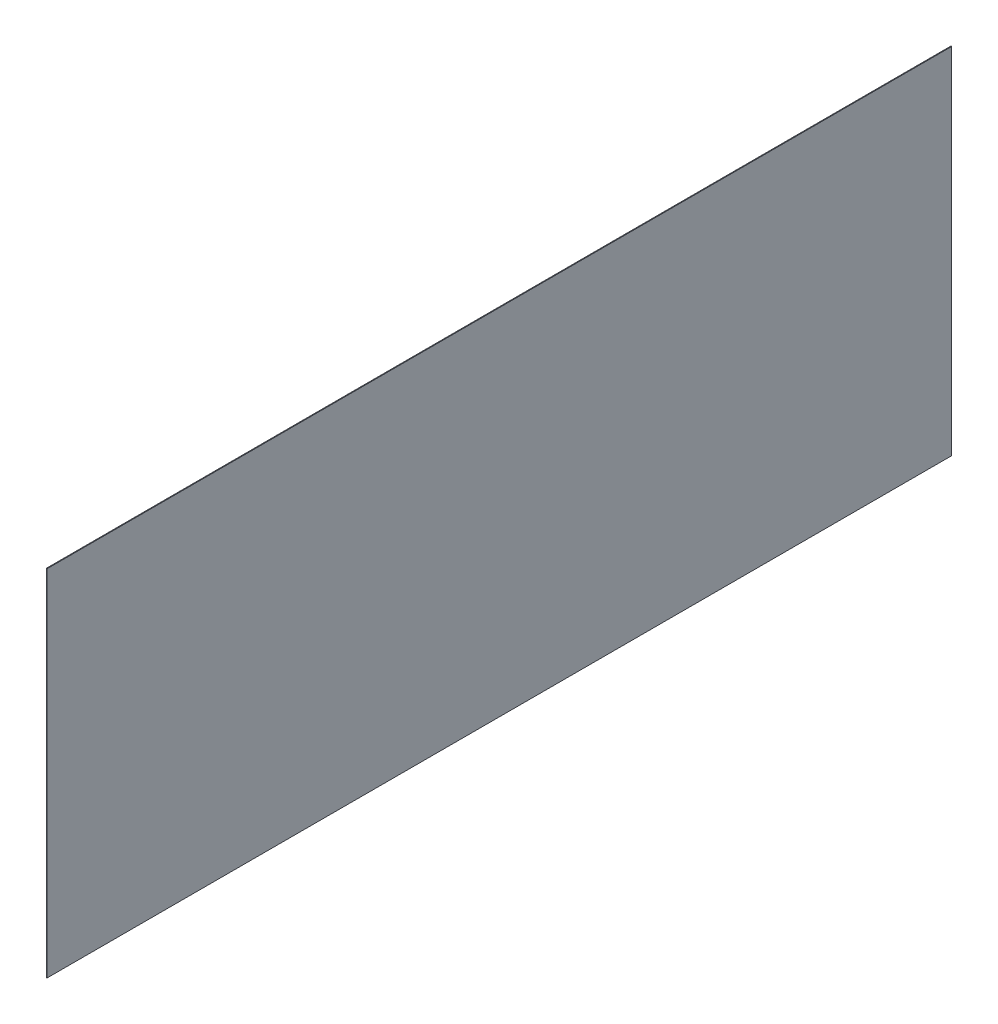
SolidWorks part; units mm, degrees
material "POLYURETHANE (11671)"
ref_plane "Front" through (0, 0, 0) normal (0, 0, 1) x (1, 0, 0)
ref_plane "Top" through (0, 0, 0) normal (0, 1, 0) x (1, 0, 0)
ref_plane "Right" through (0, 0, 0) normal (1, 0, 0) x (0, 0, -1)
sketch "Sketch1" plane through (0, 0, 0) normal (1, 0, 0) x (0, 0, -1)
  line L1 (-3009, 1179) -> (3009, 1179)
  line L2 (-3009, 1179) -> (-3009, -1179)
  line L3 (-3009, -1179) -> (3009, -1179)
  line L4 (3009, 1179) -> (3009, -1179)
  line L5 (-3009, 1179) -> (3009, -1179) construction
  line L6 (-3009, -1179) -> (3009, 1179) construction
  point P0 (0, 0)
  dimension "D1" = 6018
  dimension "D2" = 2358
extrude "Boss-Extrude1" add sketch "Sketch1" along normal blind 5
